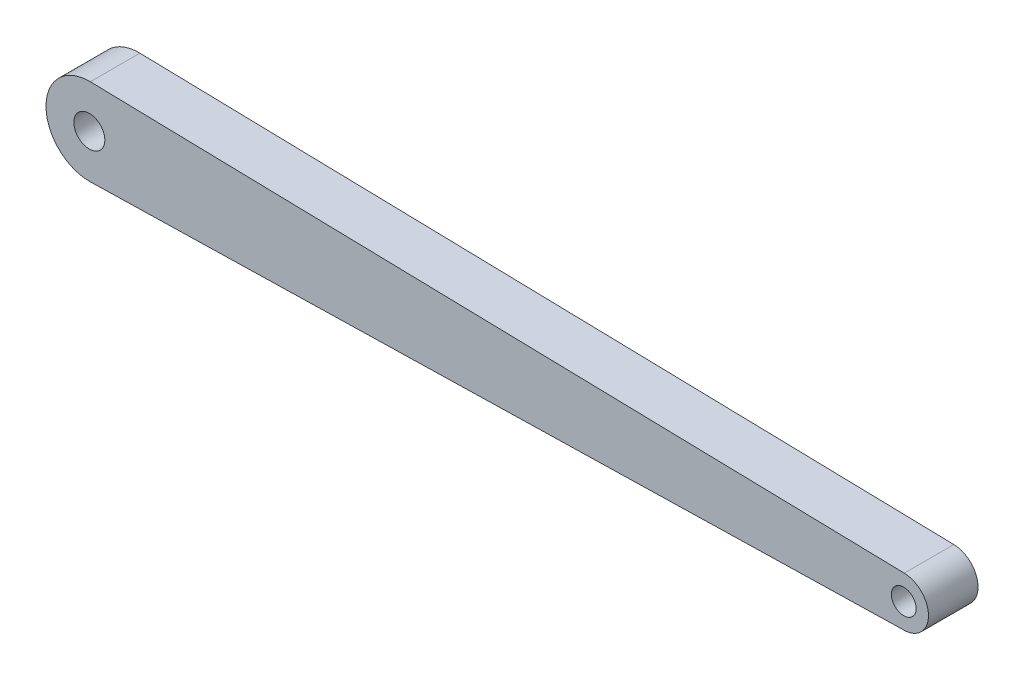
SolidWorks part; units mm, degrees
ref_plane "Front Plane" through (0, 0, 0) normal (0, 0, 1) x (1, 0, 0)
ref_plane "Top Plane" through (0, 0, 0) normal (0, 1, 0) x (1, 0, 0)
ref_plane "Right Plane" through (0, 0, 0) normal (1, 0, 0) x (0, 0, -1)
sketch "Sketch1" plane through (0, 0, 0) normal (0, 0, 1) x (1, 0, 0)
  line L0 (-1796.5636, 0) -> (60.4423, 0) construction
  line L1 (-1313.403, 69.9818) -> (0.9125, 39.9896)
  line L2 (-1313.403, -69.9818) -> (0.9125, -39.9896)
  circle A0 centre (0, 0) radius 20
  circle A1 centre (-1315, 0) radius 25
  arc A2 (-1313.403, 69.9818) -> (-1313.403, -69.9818) centre (-1315, 0) ccw
  arc A3 (0.9125, 39.9896) -> (0.9125, -39.9896) centre (0, 0) cw
  point P11 (34.5417, -20.171)
  point P12 (-2.3034, 39.9336)
  dimension "D1" = 50
  dimension "D2" = 1315
  dimension "D3" = 40
  dimension "D4" = 70
  dimension "D5" = 40
extrude "Boss-Extrude1" add sketch "Sketch1" along normal mid plane 80
